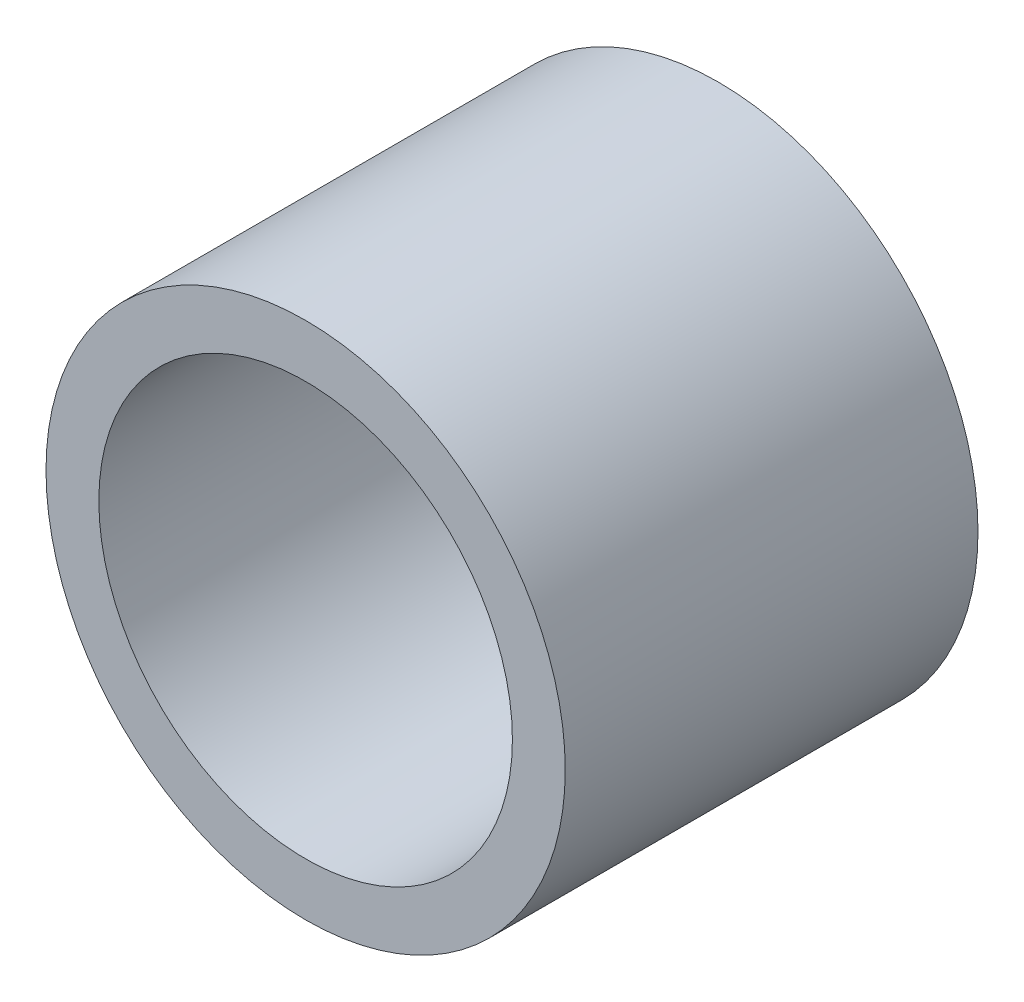
SolidWorks part; units mm, degrees
ref_plane "Front Plane" through (0, 0, 0) normal (0, 0, 1) x (1, 0, 0)
ref_plane "Top Plane" through (0, 0, 0) normal (0, 1, 0) x (1, 0, 0)
ref_plane "Right Plane" through (0, 0, 0) normal (1, 0, 0) x (0, 0, -1)
sketch "Sketch1" plane through (0, 0, 0) normal (0, 0, 1) x (1, 0, 0)
  circle A0 centre (0, 0) radius 3.9942
  circle A1 centre (0, 0) radius 3.1813
  dimension "OD" = 7.9883
  dimension "ID" = 6.3627
sketch "Sketch2" plane through (0, 0, 0) normal (1, 0, 0) x (0, 0, -1)
  line L2 (3.175, 0) -> (-3.175, 0) construction
  line L4 (-3.175, -3.9942) -> (-3.175, 3.9941) construction
  line L5 (-3.175, -3.1813) -> (3.175, -3.1813)
  line L6 (3.175, 3.1813) -> (-3.175, 3.1813)
  line L7 (3.175, -3.9942) -> (3.175, 3.9941) construction
  line L8 (-3.175, 3.9941) -> (3.175, 3.9941) construction
  line L9 (-3.175, -3.9942) -> (3.175, -3.9942) construction
  line L10 (0, 3.9942) -> (0, -3.9942) construction
  line L11 (0, 3.1813) -> (0, -3.1813) construction
  point P4 (0, -3.1813)
  point P7 (0, 3.1813)
  point P8 (0, 0)
  point P12 (-3.175, 0)
  point P15 (3.175, 0)
  point P16 (0, -3.9942)
  point P17 (0, 3.9942)
  dimension "Length" = 6.35
sketch "Sketch5" plane through (0, 0, 0) normal (0, 0, 1) x (1, 0, 0)
  circle A1 centre (0, 0) radius 3.1813
  circle A2 centre (0, 0) radius 3.1813
  circle A3 centre (0, 0) radius 3.9942
  circle A4 centre (0, 0) radius 3.9942
  dimension "D1" = 0
  dimension "D2" = 0
extrude "Boss-Extrude1" add sketch "Sketch5" along normal up to vertex (3.175 mm away) and the other way up to vertex (3.175 mm away) up to point (0, 0, 3.175) other way up to point (0, 0, -3.175)
sketch "Sketch4" plane through (0, 0, 3.175) normal (0, 0, 1) x (1, 0, 0)
  line L0 (0, 0) -> (-2.2496, 2.2496)
  line L2 (0, -3.9942) -> (0, 3.9941) construction
  circle A1 centre (0, 0) radius 3.1813 construction
  dimension "D1" = 45
equation "\"D1\"= \"Length@Sketch2\""
